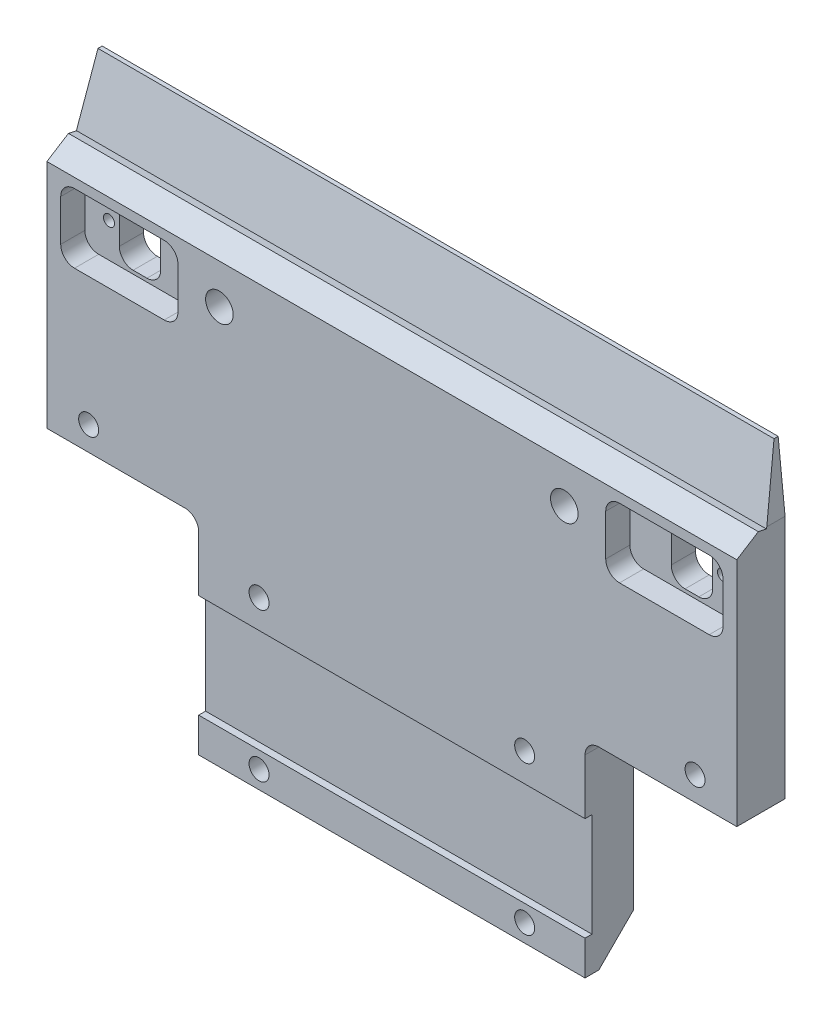
SolidWorks part; units mm, degrees
material "AISI 316 Chapa de aço inoxidável (SS)"
ref_plane "Plano frontal" through (0, 0, 0) normal (0, 0, 1) x (1, 0, 0)
ref_plane "Plano superior" through (0, 0, 0) normal (0, 1, 0) x (1, 0, 0)
ref_plane "Plano direito" through (0, 0, 0) normal (1, 0, 0) x (0, 0, -1)
sketch "Esboço1" plane through (0, 0, 0) normal (0, 0, 1) x (1, 0, 0)
  line L1 (-34.5183, -69.0325) -> (65.4817, -69.0325)
  line L2 (-34.5183, -69.0325) -> (-34.5183, -114.0325)
  line L3 (-34.5183, -114.0325) -> (65.4817, -114.0325)
  line L4 (65.4817, -69.0325) -> (65.4817, -114.0325)
  line L5 (43.4817, -114.0325) -> (-12.5183, -114.0325)
  line L6 (43.4817, -114.0325) -> (43.4817, -144.0325)
  line L7 (43.4817, -144.0325) -> (-12.5183, -144.0325)
  line L8 (-12.5183, -114.0325) -> (-12.5183, -144.0325)
  point P8 (15.4817, -144.0325)
  point P9 (15.4817, -114.0325)
  dimension "D1" = 100
  dimension "D2" = 45
  dimension "D3" = 30
  dimension "D4" = 56
  dimension "D5" = 0
extrude "Ressalto-extrusão1" add sketch "Esboço1" along normal blind 7 contours L3 L8 L7 L6 | L4 L1 L2 L3
sketch "Esboço2" plane through (-34.5183, 0, 0) normal (-1, 0, 0) x (0, 0, 1)
  line L0 (0.6, -69.0325) -> (7, -69.0325)
  line L1 (7, -69.0325) -> (0, -69.0325) construction
  line L2 (7, -69.0325) -> (7, -114.0325) construction
  line L3 (7, -69.0325) -> (7, -80.5325)
  line L4 (7, -80.5325) -> (3.8766, -78.5645)
  line L5 (3.8766, -78.5645) -> (2.7029, -78.814)
  line L6 (2.7029, -78.814) -> (0.6, -69.0325)
  dimension "D1" = 0.6
  dimension "D2" = 11.5
extrude "Corte-extrusão1" cut sketch "Esboço2" against normal through all
sketch "Esboço3" plane through (43.4817, 0, 0) normal (1, 0, 0) x (0, 0, -1)
  line L1 (0, -114.0325) -> (0, -144.0325) construction
  line L3 (-7, -144.0325) -> (0, -144.0325) construction
  line L4 (-5, -144.0325) -> (0, -139.0325)
  line L5 (-5, -144.0325) -> (0, -144.0325)
  line L6 (0, -144.0325) -> (0, -139.0325)
  dimension "D1" = 45
  dimension "D2" = 2
extrude "Corte-extrusão2" cut sketch "Esboço3" against normal through all
sketch "Esboço5" plane through (0, 0, 7) normal (0, 0, 1) x (1, 0, 0)
  line L0 (-32.5183, -81.9319) -> (-15.5183, -81.9319)
  line L9 (-15.5183, -81.9319) -> (-15.5183, -91.9319)
  line L10 (-32.5183, -91.9319) -> (-15.5183, -91.9319)
  line L11 (-32.5183, -81.9319) -> (-32.5183, -91.9319)
  line L12 (46.4817, -81.9319) -> (63.4817, -81.9319)
  line L13 (63.4817, -81.9319) -> (63.4817, -91.9319)
  line L14 (46.4817, -91.9319) -> (63.4817, -91.9319)
  line L15 (46.4817, -81.9319) -> (46.4817, -91.9319)
extrude "Corte-extrusão4" cut sketch "Esboço5" against normal blind 3.5
sketch "Esboço7" plane through (0, 0, 7) normal (0, 0, 1) x (1, 0, 0)
  line L0 (64.4776, -69.0325) -> (65.4817, -69.0325)
  line L1 (65.4817, -69.0325) -> (-34.5183, -69.0325) construction
  line L2 (65.4817, -69.0325) -> (65.4817, -78.814) construction
  line L3 (65.4817, -69.0325) -> (65.4817, -78.5645)
  line L4 (65.4817, -78.5645) -> (64.4776, -69.0325)
  line L5 (-34.5183, -78.5645) -> (-33.5141, -69.0325)
  line L6 (-34.5183, -78.5645) -> (-34.5183, -80.5325) construction
  line L7 (65.4817, -78.5645) -> (-34.5183, -78.5645) construction
  line L8 (-33.5141, -69.0325) -> (-34.5183, -69.0325)
  line L9 (-34.5183, -69.0325) -> (-34.5183, -78.814) construction
  line L10 (-34.5183, -69.0325) -> (-34.5183, -78.5645)
extrude "Corte-extrusão6" cut sketch "Esboço7" against normal blind 24
fillet "Filete1" radius 2 8 edges at (-15.5183, -91.9319, 5.25) (-15.5183, -81.9319, 5.25) (-32.5183, -91.9319, 5.25) (-32.5183, -81.9319, 5.25) (46.4817, -81.9319, 5.25) (46.4817, -91.9319, 5.25) (63.4817, -91.9319, 5.25) (63.4817, -81.9319, 5.25)
fillet "Filete2" radius 2 2 edges at (43.4817, -114.0325, 3.5) (-12.5183, -114.0325, 3.5)
sketch "Esboço8" plane through (0, 0, 7) normal (0, 0, 1) x (1, 0, 0)
  line L0 (-27.5183, -82.4319) -> (-21.5183, -82.4319)
  line L9 (-21.5183, -82.4319) -> (-21.5183, -91.4319)
  line L10 (-27.5183, -91.4319) -> (-21.5183, -91.4319)
  line L11 (-27.5183, -82.4319) -> (-27.5183, -91.4319)
  line L12 (52.4817, -82.4319) -> (58.4817, -82.4319)
  line L13 (58.4817, -82.4319) -> (58.4817, -91.4319)
  line L14 (52.4817, -91.4319) -> (58.4817, -91.4319)
  line L15 (52.4817, -82.4319) -> (52.4817, -91.4319)
  circle A0 centre (59.9817, -86.9319) radius 0.8
  circle A1 centre (-29.0183, -86.9319) radius 0.8
extrude "Corte-extrusão7" cut sketch "Esboço8" against normal blind 24
fillet "Filete3" radius 2 8 edges at (58.4817, -82.4319, 1.75) (52.4817, -82.4319, 1.75) (52.4817, -91.4319, 1.75) (58.4817, -91.4319, 1.75) (-21.5183, -91.4319, 1.75) (-27.5183, -91.4319, 1.75) (-21.5183, -82.4319, 1.75) (-27.5183, -82.4319, 1.75)
sketch "Esboço9" plane through (0, 0, 7) normal (0, 0, 1) x (1, 0, 0)
  line L0 (-12.5183, -116.0325) -> (-12.5183, -144.0325) construction
  line L1 (-12.5183, -124.0325) -> (43.4817, -124.0325)
  line L2 (-12.5183, -124.0325) -> (-12.5183, -139.0325)
  line L3 (-12.5183, -139.0325) -> (43.4817, -139.0325)
  line L4 (43.4817, -124.0325) -> (43.4817, -139.0325)
  line L5 (43.4817, -116.0325) -> (43.4817, -144.0325) construction
  line L6 (43.4817, -144.0325) -> (-12.5183, -144.0325) construction
  dimension "D1" = 15
  dimension "D2" = 5
extrude "Corte-extrusão8" cut sketch "Esboço9" against normal blind 1
sketch "Esboço10" plane through (0, 0, 7) normal (0, 0, 1) x (1, 0, 0)
  circle A0 centre (-3.7683, -119.906) radius 1.45
  circle A1 centre (34.7317, -119.906) radius 1.45
  circle A2 centre (34.7317, -141.4575) radius 1.45
  circle A3 centre (-3.7683, -141.4575) radius 1.45
  dimension "D1" = 2.9
  dimension "D2" = 2.9
  dimension "D3" = 2.9
  dimension "D4" = 2.9
extrude "Corte-extrusão9" cut sketch "Esboço10" against normal blind 17
sketch "Esboço11" plane through (0, 0, 0) normal (0, 0, -1) x (-1, 0, 0)
  circle A0 centre (-40.4817, -86.2924) radius 2
  circle A1 centre (9.5183, -86.2924) radius 2
extrude "Corte-extrusão10" cut sketch "Esboço11" against normal blind 15
chamfer "Chanfro1" distance 2 angle 45 2 edges at (38.4817, -86.2924, 0) (-11.5183, -86.2924, 0)
sketch "Esboço12" plane through (0, 0, 0) normal (0, 0, -1) x (-1, 0, 0)
  circle A0 centre (-59.4317, -110.5325) radius 1.45
  circle A1 centre (28.4683, -110.5325) radius 1.45
  dimension "D1" = 2.9
  dimension "D2" = 2.9
extrude "Corte-extrusão11" cut sketch "Esboço12" against normal blind 15
sketch "Esboço13" plane through (65.4817, 0, 0) normal (1, 0, 0) x (0, 0, -1)
  line L0 (-2.7029, -78.814) -> (-0.6, -69.0325)
  line L1 (-0.6, -69.0325) -> (0, -69.0325)
  line L2 (0, -69.0325) -> (0, -79.7728)
  line L3 (0, -78.5645) -> (0, -114.0325) construction
  dimension "D1" = 12.133
